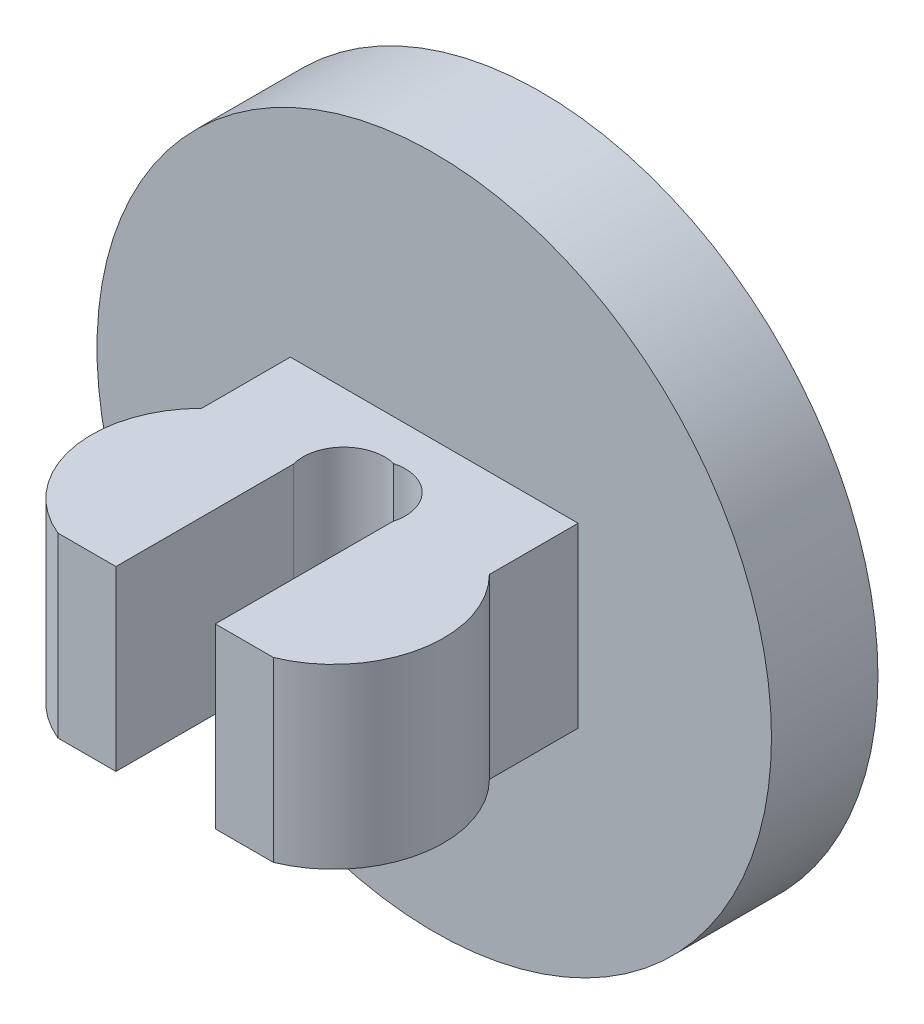
SolidWorks part; units mm, degrees
ref_plane "Front Plane" through (0, 0, 0) normal (0, 0, 1) x (1, 0, 0)
ref_plane "Top Plane" through (0, 0, 0) normal (0, 1, 0) x (1, 0, 0)
ref_plane "Right Plane" through (0, 0, 0) normal (1, 0, 0) x (0, 0, -1)
sketch "Sketch1" plane through (0, 0, 0) normal (0, 0, 1) x (1, 0, 0)
  circle A0 centre (0, 0) radius 9.5
  dimension "D1" = 19
extrude "Boss-Extrude1" add sketch "Sketch1" along normal blind 3
sketch "Sketch3" plane through (0, 0, 0) normal (0, 1, 0) x (1, 0, 0)
  line L0 (-9.5, -3) -> (9.5, -3) construction
  line L1 (0, 0) -> (0, -14.3724) construction
  line L8 (-4.053, -5.5) -> (-4.053, -3)
  line L11 (-3.0361, -10.5668) -> (-1.4, -10.5668)
  line L12 (-1.4, -10.5668) -> (-1.4, -5.5668)
  line L13 (-4.053, -3) -> (4.053, -3)
  line L14 (1.4, -10.5668) -> (1.4, -5.5668)
  line L15 (3.0361, -10.5668) -> (1.4, -10.5668)
  line L16 (4.053, -5.5) -> (4.053, -3)
  arc A8 (-1.4, -5.5668) -> (0, -4.1424) centre (-0.289, -5.2586) cw
  arc A10 (-3.0361, -10.5668) -> (-4.053, -5.5) centre (-1.8537, -7.6941) cw
  arc A11 (3.0361, -10.5668) -> (4.053, -5.5) centre (1.8537, -7.6941) ccw
  arc A12 (1.4, -5.5668) -> (0, -4.1424) centre (0.289, -5.2586) ccw
  point P21 (0, -3)
  point P25 (0, -3)
  dimension "D5" = 3.1066
  dimension "D8" = 1.153
  dimension "D1" = 2.653
  dimension "D2" = 1.4
  dimension "D3" = 1.6361
  dimension "D4" = 5.0668
  dimension "D6" = 5
  dimension "D7" = 1.4244
  dimension "D9" = 2.5
extrude "Boss-Extrude2" add sketch "Sketch3" along normal mid plane 5
